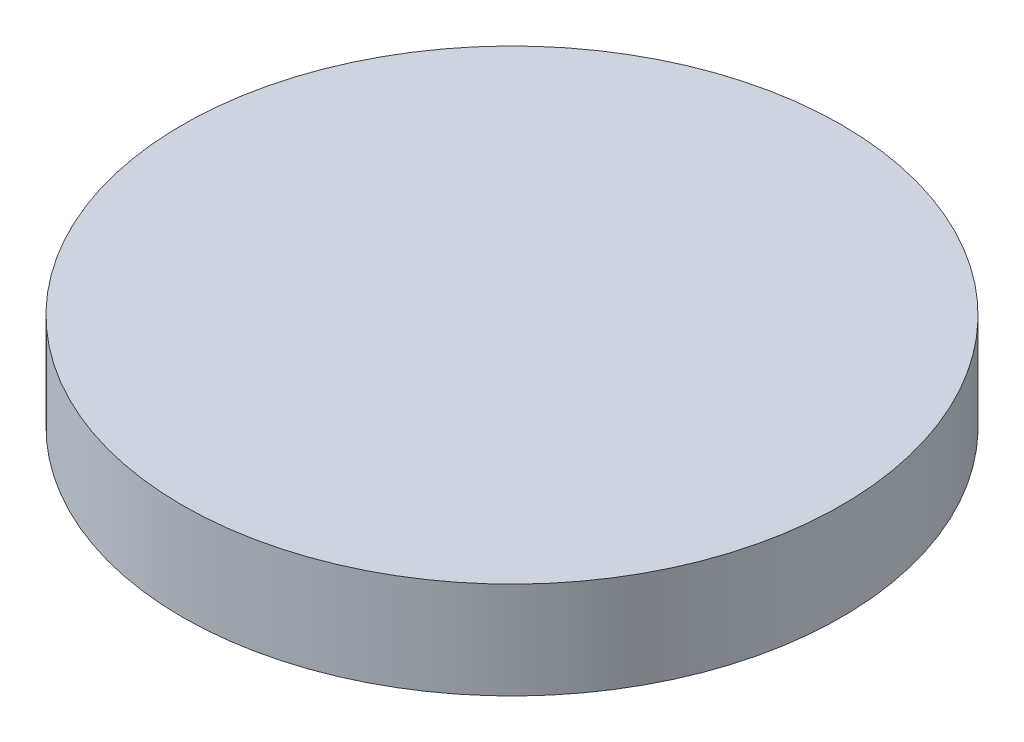
SolidWorks part; units mm, degrees
ref_plane "Front Plane" through (0, 0, 0) normal (0, 0, 1) x (1, 0, 0)
ref_plane "Top Plane" through (0, 0, 0) normal (0, 1, 0) x (1, 0, 0)
ref_plane "Right Plane" through (0, 0, 0) normal (1, 0, 0) x (0, 0, -1)
sketch "Sketch1" plane through (0, 0, 0) normal (0, 1, 0) x (1, 0, 0)
  circle A0 centre (-21.4426, 0) radius 81.6443
extrude "Boss-Extrude1" add sketch "Sketch1" along normal blind 24
